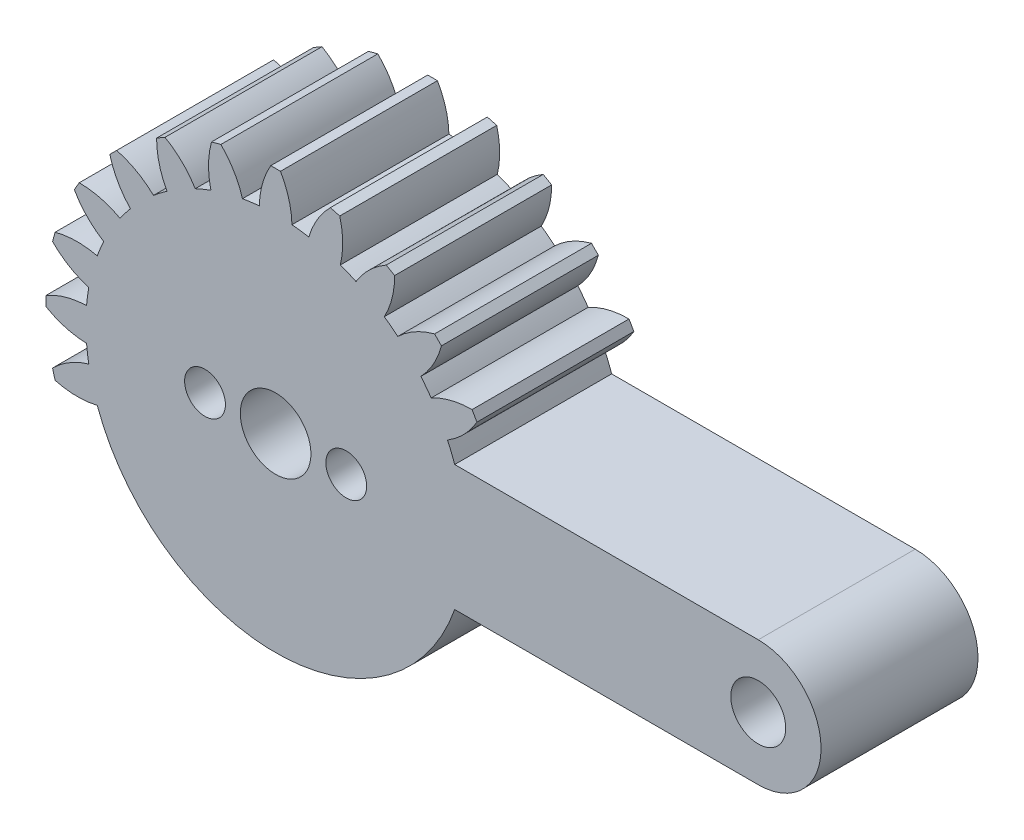
SolidWorks part; units mm, degrees
ref_plane "Front Plane" through (0, 0, 0) normal (0, 0, 1) x (1, 0, 0)
ref_plane "Top Plane" through (0, 0, 0) normal (0, 1, 0) x (1, 0, 0)
ref_plane "Right Plane" through (0, 0, 0) normal (1, 0, 0) x (0, 0, -1)
sketch "Sketch1" plane through (0, 0, 0) normal (0, 0, 1) x (1, 0, 0)
  line L0 (0, 0) -> (30.75, 0) construction
  line L1 (0, -14.63) -> (0, 14.63) construction
  line L2 (-0.31, 14.63) -> (0.31, 14.63)
  line L3 (3.4871, 14.2117) -> (4.086, 14.0513)
  line L4 (7.0465, 12.825) -> (7.5835, 12.515)
  line L5 (10.1258, 10.5642) -> (10.5642, 10.1258)
  line L6 (12.515, 7.5835) -> (12.825, 7.0465)
  line L7 (14.0513, 4.086) -> (14.2117, 3.4871)
  line L8 (14.63, 0.31) -> (14.63, -0.31)
  line L9 (14.2117, -3.4871) -> (14.0513, -4.086)
  line L10 (12.825, -7.0465) -> (12.515, -7.5835)
  line L11 (10.5642, -10.1258) -> (10.1258, -10.5642)
  line L12 (7.5835, -12.515) -> (7.0465, -12.825)
  line L13 (4.086, -14.0513) -> (3.4871, -14.2117)
  line L14 (0.31, -14.63) -> (-0.31, -14.63)
  line L15 (-3.4871, -14.2117) -> (-4.086, -14.0513)
  line L16 (-7.0465, -12.825) -> (-7.5835, -12.515)
  line L17 (-10.1258, -10.5642) -> (-10.5642, -10.1258)
  line L18 (-12.515, -7.5835) -> (-12.825, -7.0465)
  line L19 (-14.0513, -4.086) -> (-14.2117, -3.4871)
  line L20 (-14.63, -0.31) -> (-14.63, 0.31)
  line L21 (-14.2117, 3.4871) -> (-14.0513, 4.086)
  line L22 (-12.825, 7.0465) -> (-12.515, 7.5835)
  line L23 (-10.5642, 10.1258) -> (-10.1258, 10.5642)
  line L24 (-7.5835, 12.515) -> (-7.0465, 12.825)
  line L25 (-4.086, 14.0513) -> (-3.4871, 14.2117)
  line L26 (30.75, -4) -> (30.75, 4) construction
  line L27 (30.75, 4) -> (11.4091, 4)
  line L28 (30.75, -4) -> (11.4091, -4)
  circle A0 centre (0, 0) radius 1.75
  circle A1 centre (0, 0) radius 12.09
  circle A2 centre (30.75, 0) radius 1.75
  arc A3 (-1.04, 12.0452) -> (-0.31, 14.63) centre (4.3585, 11.9161) cw
  arc A4 (1.04, 12.0452) -> (0.31, 14.63) centre (-4.3585, 11.9161) ccw
  arc A5 (4.1221, 11.3656) -> (4.086, 14.0513) centre (-1.1258, 12.6381) ccw
  arc A6 (2.113, 11.9039) -> (3.4871, 14.2117) centre (7.294, 10.382) cw
  arc A7 (6.9233, 9.9114) -> (7.5835, 12.515) centre (2.1835, 12.4988) ccw
  arc A8 (5.1219, 10.9514) -> (7.0465, 12.825) centre (9.7326, 8.1404) cw
  arc A9 (9.2526, 7.7818) -> (10.5642, 10.1258) centre (5.344, 11.5078) ccw
  arc A10 (7.7818, 9.2526) -> (10.1258, 10.5642) centre (11.5078, 5.344) cw
  arc A11 (10.9514, 5.1219) -> (12.825, 7.0465) centre (8.1404, 9.7326) ccw
  arc A12 (9.9114, 6.9233) -> (12.515, 7.5835) centre (12.4988, 2.1835) cw
  arc A13 (11.9039, 2.113) -> (14.2117, 3.4871) centre (10.382, 7.294) ccw
  arc A14 (11.3656, 4.1221) -> (14.0513, 4.086) centre (12.6381, -1.1258) cw
  arc A15 (12.0452, -1.04) -> (14.63, -0.31) centre (11.9161, 4.3585) ccw
  arc A16 (12.0452, 1.04) -> (14.63, 0.31) centre (11.9161, -4.3585) cw
  arc A17 (11.3656, -4.1221) -> (14.0513, -4.086) centre (12.6381, 1.1258) ccw
  arc A18 (11.9039, -2.113) -> (14.2117, -3.4871) centre (10.382, -7.294) cw
  arc A19 (9.9114, -6.9233) -> (12.515, -7.5835) centre (12.4988, -2.1835) ccw
  arc A20 (10.9514, -5.1219) -> (12.825, -7.0465) centre (8.1404, -9.7326) cw
  arc A21 (7.7818, -9.2526) -> (10.1258, -10.5642) centre (11.5078, -5.344) ccw
  arc A22 (9.2526, -7.7818) -> (10.5642, -10.1258) centre (5.344, -11.5078) cw
  arc A23 (5.1219, -10.9514) -> (7.0465, -12.825) centre (9.7326, -8.1404) ccw
  arc A24 (6.9233, -9.9114) -> (7.5835, -12.515) centre (2.1835, -12.4988) cw
  arc A25 (2.113, -11.9039) -> (3.4871, -14.2117) centre (7.294, -10.382) ccw
  arc A26 (4.1221, -11.3656) -> (4.086, -14.0513) centre (-1.1258, -12.6381) cw
  arc A27 (-1.04, -12.0452) -> (-0.31, -14.63) centre (4.3585, -11.9161) ccw
  arc A28 (1.04, -12.0452) -> (0.31, -14.63) centre (-4.3585, -11.9161) cw
  arc A29 (-4.1221, -11.3656) -> (-4.086, -14.0513) centre (1.1258, -12.6381) ccw
  arc A30 (-2.113, -11.9039) -> (-3.4871, -14.2117) centre (-7.294, -10.382) cw
  arc A31 (-6.9233, -9.9114) -> (-7.5835, -12.515) centre (-2.1835, -12.4988) ccw
  arc A32 (-5.1219, -10.9514) -> (-7.0465, -12.825) centre (-9.7326, -8.1404) cw
  arc A33 (-9.2526, -7.7818) -> (-10.5642, -10.1258) centre (-5.344, -11.5078) ccw
  arc A34 (-7.7818, -9.2526) -> (-10.1258, -10.5642) centre (-11.5078, -5.344) cw
  arc A35 (-10.9514, -5.1219) -> (-12.825, -7.0465) centre (-8.1404, -9.7326) ccw
  arc A36 (-9.9114, -6.9233) -> (-12.515, -7.5835) centre (-12.4988, -2.1835) cw
  arc A37 (-11.9039, -2.113) -> (-14.2117, -3.4871) centre (-10.382, -7.294) ccw
  arc A38 (-11.3656, -4.1221) -> (-14.0513, -4.086) centre (-12.6381, 1.1258) cw
  arc A39 (-12.0452, 1.04) -> (-14.63, 0.31) centre (-11.9161, -4.3585) ccw
  arc A40 (-12.0452, -1.04) -> (-14.63, -0.31) centre (-11.9161, 4.3585) cw
  arc A41 (-11.3656, 4.1221) -> (-14.0513, 4.086) centre (-12.6381, -1.1258) ccw
  arc A42 (-11.9039, 2.113) -> (-14.2117, 3.4871) centre (-10.382, 7.294) cw
  arc A43 (-9.9114, 6.9233) -> (-12.515, 7.5835) centre (-12.4988, 2.1835) ccw
  arc A44 (-10.9514, 5.1219) -> (-12.825, 7.0465) centre (-8.1404, 9.7326) cw
  arc A45 (-7.7818, 9.2526) -> (-10.1258, 10.5642) centre (-11.5078, 5.344) ccw
  arc A46 (-9.2526, 7.7818) -> (-10.5642, 10.1258) centre (-5.344, 11.5078) cw
  arc A47 (-5.1219, 10.9514) -> (-7.0465, 12.825) centre (-9.7326, 8.1404) ccw
  arc A48 (-6.9233, 9.9114) -> (-7.5835, 12.515) centre (-2.1835, 12.4988) cw
  arc A49 (-2.113, 11.9039) -> (-3.4871, 14.2117) centre (-7.294, 10.382) ccw
  arc A50 (-4.1221, 11.3656) -> (-4.086, 14.0513) centre (1.1258, 12.6381) cw
  arc A51 (30.75, -4) -> (30.75, 4) centre (30.75, 0) ccw
  point P9 (0, 0)
  point P155 (0, 0)
  point P158 (30.75, 0)
  dimension "D2" = 3.5
  dimension "D3" = 3.5
  dimension "D4" = 24.18
  dimension "D6" = 5.4
  dimension "D10" = 8
  dimension "D1" = 30.75
  dimension "D5" = 29.26
  dimension "D7" = 0.31
  dimension "D8" = 1.04
  dimension "D9" = 24
extrude "Boss-Extrude1" add sketch "Sketch1" along normal blind 10 contours A1 | L28 A51 L27 L7 A13 A1 A16 L8 A15 A18 L9 A2 | A12 A1 A11 L6 | A10 A1 A9 L5 | A8 A1 A7 L4 | A6 A1 A5 L3 | A1 A4 L2 A3 | A50 A1 A49 L25 | A48 A1 A47 L24 | A46 A1 A45 L23 | A44 A1 A43 L22 | A42 A1 A41 L21 | A40 A1 A39 L20 | A38 A1 A37 L19 | A1 A13 L7 L27 | A16 A1 A15 L8 | A18 A1 L28 L9
sketch "Sketch2" plane through (0, 0, 10) normal (0, 0, 1) x (1, 0, 0)
  line L0 (-4.5, 0) -> (4.5, 0) construction
  circle A0 centre (-4.5, 0) radius 1.3
  circle A1 centre (4.5, 0) radius 1.3
  circle A2 centre (0, 0) radius 2.25
  point P5 (0, 0)
  dimension "D2" = 2.6
  dimension "D3" = 2.6
  dimension "D4" = 4.5
  dimension "D1" = 9
extrude "Cut-Extrude1" cut sketch "Sketch2" against normal through all
